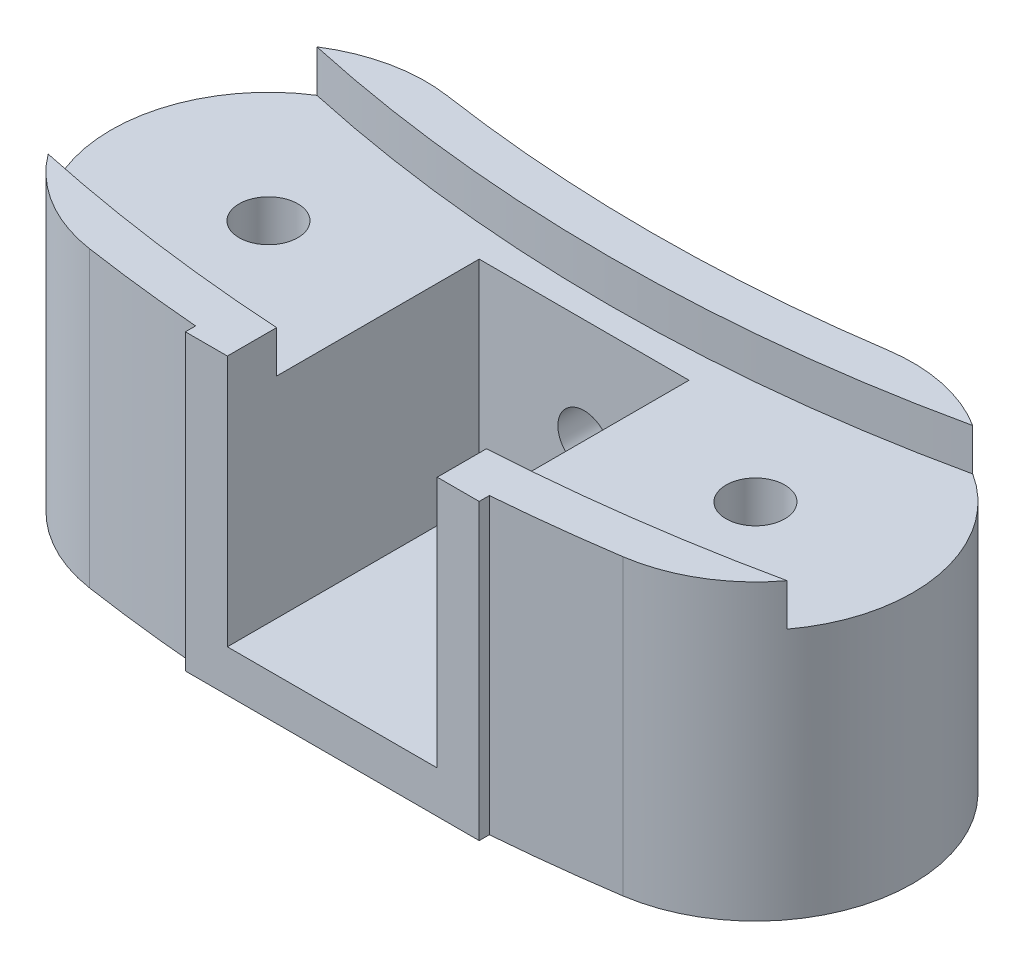
SolidWorks part; units mm, degrees
material "ABS"
ref_plane "Front Plane" through (0, 0, 0) normal (0, 0, 1) x (1, 0, 0)
ref_plane "Top Plane" through (0, 0, 0) normal (0, 1, 0) x (1, 0, 0)
ref_plane "Right Plane" through (0, 0, 0) normal (1, 0, 0) x (0, 0, -1)
sketch "Sketch2" plane through (0, 0, 0) normal (0, 1, 0) x (1, 0, 0)
  line L0 (0, 78.5) -> (25.0188, -14.8716) construction
  line L1 (0, 0) -> (0, 91.8096) construction
  line L2 (0, 78.5) -> (-25.3158, -15.9799) construction
  line L3 (0, 78.5) -> (-14.8004, -20.5315) construction
  line L4 (0, 78.5) -> (14.5313, -18.7312) construction
  arc A0 (-10.4945, 8.2799) -> (10.4945, 8.2799) centre (0, 78.5) ccw
  arc A1 (-12.7116, -6.5554) -> (12.7116, -6.5554) centre (0, 78.5) ccw
  circle A4 centre (0, 78.5) radius 78.5 construction
  circle A6 centre (0, 78.5) radius 73 construction
  circle A7 centre (0, 78.5) radius 84 construction
  circle A8 centre (0, 78.5) radius 86 construction
  circle A9 centre (0, 78.5) radius 71 construction
  circle A11 centre (11.603, 0.8623) radius 1.4
  circle A12 centre (-11.603, 0.8623) radius 1.4
  arc A13 (-10.4945, 8.2799) -> (-7.1774, -5.1928) centre (-11.603, 0.8623) ccw
  arc A14 (7.1774, -5.1928) -> (10.4945, 8.2799) centre (11.603, 0.8623) ccw
  point P6 (71, 78.5)
  point P13 (86, 78.5)
  dimension "D1" = 146
  dimension "D2" = 168
  dimension "D3" = 5.5
  dimension "D8" = 142
  dimension "D9" = 86
  dimension "D6" = 6.5
  dimension "D11" = 71
  dimension "D12" = 2.8
  dimension "D13" = 2.8
  dimension "D4" = 15
  dimension "D5" = 15
  dimension "D10" = 6.5
  dimension "D7" = 2
extrude "Boss-Extrude1" add sketch "Sketch2" along normal blind 12
sketch "Sketch14" plane through (0, 12, 0) normal (0, 1, 0) x (1, 0, 0)
  arc A0 (-15.626, 7.192) -> (15.626, 7.192) centre (0, 78.5) ccw
  arc A1 (-17.6056, -3.6343) -> (17.6056, -3.6343) centre (0, 78.5) ccw
  arc A2 (-12.7116, -6.5554) -> (12.7116, -6.5554) centre (0, 78.5) ccw construction
  arc A3 (-10.4945, 8.2799) -> (10.4945, 8.2799) centre (0, 78.5) ccw construction
  arc A4 (-10.4945, 8.2799) -> (-12.7116, -6.5554) centre (-11.603, 0.8623) ccw construction
  arc A5 (-10.4945, 8.2799) -> (-12.7116, -6.5554) centre (-11.603, 0.8623) ccw
  arc A6 (12.7116, -6.5554) -> (10.4945, 8.2799) centre (11.603, 0.8623) ccw construction
  arc A7 (12.7116, -6.5554) -> (10.4945, 8.2799) centre (11.603, 0.8623) ccw
  arc A9 (-10.4945, 8.2799) -> (10.4945, 8.2799) centre (0, 78.5) ccw
  arc A11 (-12.7116, -6.5554) -> (12.7116, -6.5554) centre (0, 78.5) ccw
  dimension "D2" = 84
  dimension "D3" = 73
extrude "Boss-Extrude5" add sketch "Sketch14" along normal blind 2
ref_plane "Plane4" through (0, 6, 0) normal (0, 1, 0) x (1, 0, 0)
ref_plane "Plane1" through (0, 0, 7.7) normal (0, 0, 1) x (1, 0, 0)
sketch "Sketch3" plane through (0, 0, 7.7) normal (0, 0, 1) x (1, 0, 0)
  line L1 (0, 0) -> (0, 14) construction
  line L2 (-12.7116, 0) -> (12.7116, 0) construction
  line L3 (12.7116, 14) -> (-12.7116, 14) construction
  line L4 (-7, 14) -> (-7, 0)
  line L5 (-7, 0) -> (7, 0)
  line L6 (7, 0) -> (7, 14)
  line L7 (7, 14) -> (-7, 14)
  circle A0 centre (0, 7) radius 7 construction
extrude "Boss-Extrude2" add sketch "Sketch3" against normal up to body separate body contours L6 L7 L4 L5
ref_plane "Plane5" through (0, 0, -8.2799) normal (0, 0, -1) x (-1, 0, 0)
sketch "Sketch15" plane through (0, 0, 7.7) normal (0, 0, 1) x (1, 0, 0)
  line L0 (-5, 14) -> (-5, 2)
  line L1 (-5, 2) -> (5, 2)
  line L2 (5, 2) -> (5, 14)
  line L3 (5, 12) -> (-5, 12)
  line L4 (7, 0) -> (7, 14)
  line L5 (7, 14) -> (-7, 14)
  line L6 (-7, 14) -> (-7, 0)
  line L7 (-7, 0) -> (7, 0)
  line L8 (7, 0) -> (7, 14)
  line L9 (7, 14) -> (-7, 14)
  line L10 (-7, 14) -> (-7, 0)
  line L11 (-7, 0) -> (7, 0)
  line L12 (-5, 12) -> (-5, 2) construction
  line L13 (5, 2) -> (5, 12) construction
  line M6 (7, 14) -> (-7, 14)
  dimension "D1" = 0
  dimension "D2" = 2
extrude "Cut-Extrude1" cut sketch "Sketch15" against normal blind 12 contours L2 L3 L0 L1 | L3 L2 L0 M6
sketch "Sketch16" plane through (0, 0, -4.3) normal (0, 0, 1) x (1, 0, 0)
  circle A0 centre (0, 7) radius 1.25
extrude "Cut-Extrude2" cut sketch "Sketch16" against normal through all
